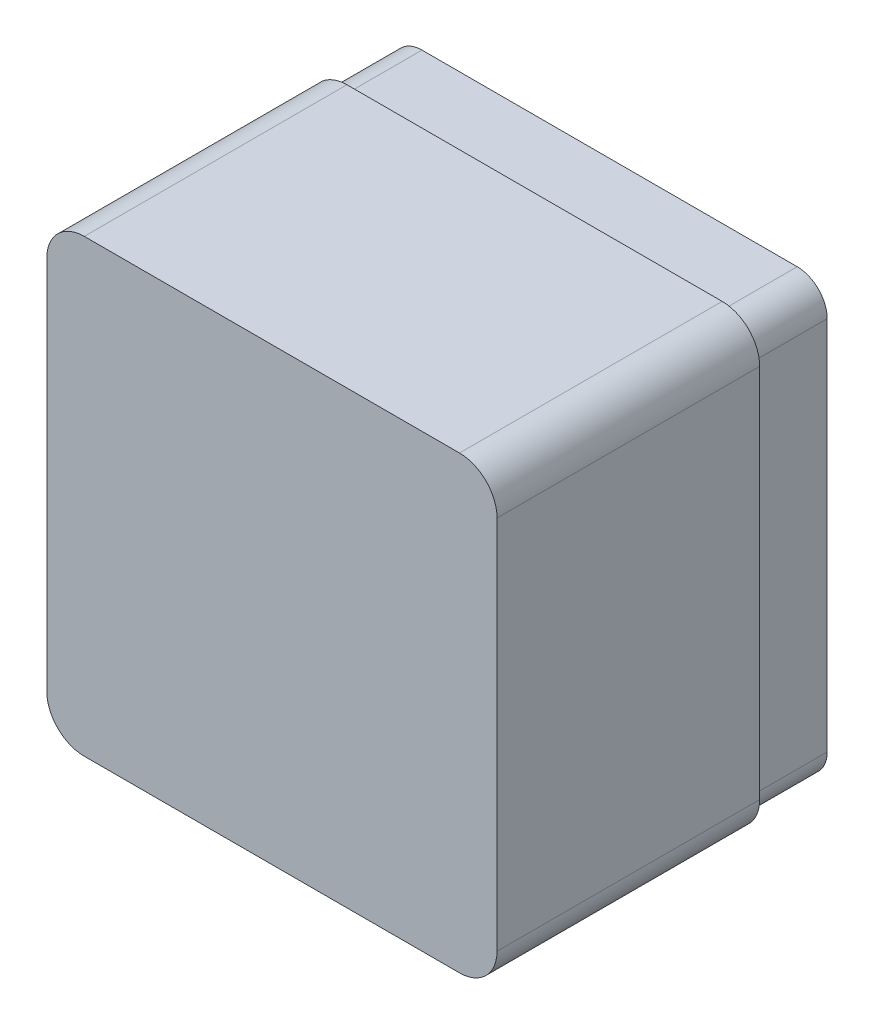
SolidWorks part; units mm, degrees
ref_plane "Front Plane" through (0, 0, 0) normal (0, 0, 1) x (1, 0, 0)
ref_plane "Top Plane" through (0, 0, 0) normal (0, 1, 0) x (1, 0, 0)
ref_plane "Right Plane" through (0, 0, 0) normal (1, 0, 0) x (0, 0, -1)
sketch "Sketch1" plane through (0, 0, 0) normal (0, 0, 1) x (1, 0, 0)
  line L1 (-60, -60) -> (60, -60)
  line L2 (-60, -60) -> (-60, 60)
  line L3 (-60, 60) -> (60, 60)
  line L4 (60, -60) -> (60, 60)
  line L5 (-60, -60) -> (60, 60) construction
  line L6 (-60, 60) -> (60, -60) construction
  point P0 (0, 0)
  dimension "D1" = 120
  dimension "D2" = 120
extrude "Boss-Extrude1" add sketch "Sketch1" along normal blind 90
fillet "Fillet1" radius 10 4 edges at (-60, 60, 45) (-60, -60, 45) (60, -60, 45) (60, 60, 45)
shell "Shell1" thickness 4
sketch "Sketch6" plane through (0, 0, 0) normal (0, 0, -1) x (-1, 0, 0)
  line L0 (58, -50) -> (58, 50)
  line L1 (50, 58) -> (-50, 58)
  line L2 (-58, 50) -> (-58, -50)
  line L3 (-50, -58) -> (50, -58)
  line L4 (60, -50) -> (60, 50)
  line L5 (50, 60) -> (-50, 60)
  line L6 (-60, 50) -> (-60, -50)
  line L7 (-50, -60) -> (50, -60)
  line L8 (60, -50) -> (60, 50) construction
  line L9 (50, 60) -> (-50, 60) construction
  line L10 (-60, 50) -> (-60, -50) construction
  line L11 (-50, -60) -> (50, -60) construction
  arc A0 (58, 50) -> (50, 58) centre (50, 50) ccw
  arc A1 (-50, 58) -> (-58, 50) centre (-50, 50) ccw
  arc A2 (-58, -50) -> (-50, -58) centre (-50, -50) ccw
  arc A3 (50, -58) -> (58, -50) centre (50, -50) ccw
  arc A4 (60, 50) -> (50, 60) centre (50, 50) ccw
  arc A5 (-50, 60) -> (-60, 50) centre (-50, 50) ccw
  arc A6 (-60, -50) -> (-50, -60) centre (-50, -50) ccw
  arc A7 (50, -60) -> (60, -50) centre (50, -50) ccw
  arc A8 (60, 50) -> (50, 60) centre (50, 50) ccw construction
  arc A9 (-50, 60) -> (-60, 50) centre (-50, 50) ccw construction
  arc A10 (-60, -50) -> (-50, -60) centre (-50, -50) ccw construction
  arc A11 (50, -60) -> (60, -50) centre (50, -50) ccw construction
  dimension "D1" = 0
  dimension "D2" = 2
extrude "Cut-Extrude5" cut sketch "Sketch6" against normal blind 20 flip side to cut
